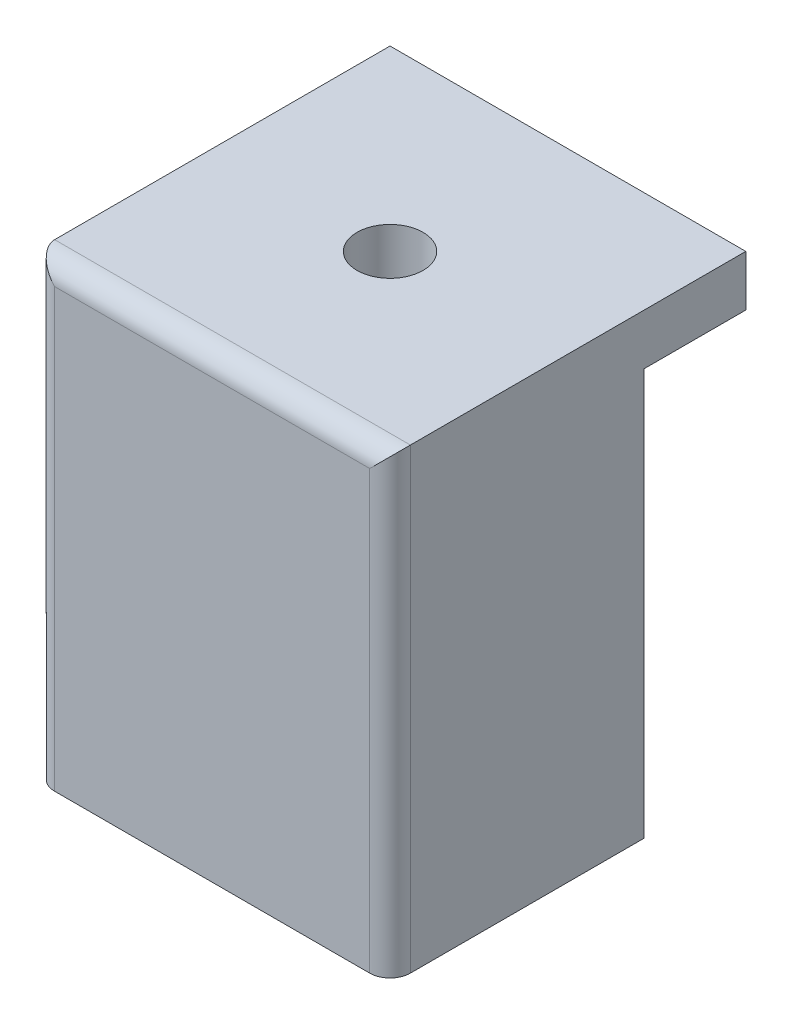
SolidWorks part; units mm, degrees
ref_plane "Front Plane" through (0, 0, 0) normal (0, 0, 1) x (1, 0, 0)
ref_plane "Top Plane" through (0, 0, 0) normal (0, 1, 0) x (1, 0, 0)
ref_plane "Right Plane" through (0, 0, 0) normal (1, 0, 0) x (0, 0, -1)
sketch "Sketch1" plane through (0, 0, 0) normal (0, 1, 0) x (1, 0, 0)
  line L0 (-17.5, 7.5) -> (-7.5, 7.5)
  line L2 (-7.5, 7.5) -> (-7.5, -7.5)
  line L3 (-7.5, -7.5) -> (7.5, -7.5)
  line L4 (7.5, 7.5) -> (7.5, -7.5)
  line L5 (-7.5, 7.5) -> (7.5, -7.5) construction
  line L6 (-7.5, -7.5) -> (7.5, 7.5) construction
  line L8 (-17.5, 7.5) -> (-17.5, -17.5)
  line L9 (-17.5, -17.5) -> (17.5, -17.5)
  line L10 (17.5, 7.5) -> (17.5, -17.5)
  line L11 (-7.5, 7.5) -> (17.5, -17.5) construction
  line L12 (-17.5, -17.5) -> (7.5, 7.5) construction
  line L13 (7.5, 7.5) -> (17.5, 7.5)
  point P0 (0, 0)
  point P6 (0, 0)
  dimension "D1" = 15
  dimension "D2" = 15
  dimension "D3" = 10
  dimension "D4" = 10
  dimension "D5" = 10
extrude "Boss-Extrude1" add sketch "Sketch1" along normal blind 45
sketch "Sketch2" plane through (0, 0, 7.5) normal (0, 0, -1) x (-1, 0, 0)
  line L0 (7.5, 45) -> (7.5, 0) construction
  line L1 (-7.5, 45) -> (7.5, 45)
  line L2 (-7.5, 45) -> (-7.5, 35)
  line L3 (-7.5, 35) -> (7.5, 35)
  line L4 (7.5, 45) -> (7.5, 35)
  line L5 (0, 20) -> (0, 0) construction
  line L6 (-7.5, 20) -> (7.5, 20) construction
  line L7 (-7.5, 45) -> (-7.5, 0) construction
  line L8 (7.5, 45) -> (7.5, 0) construction
  line L9 (0, 35) -> (0, 20) construction
  line L10 (0, 27.5) -> (7.5, 27.5) construction
  line L11 (-7.5, 20) -> (7.5, 20)
  line L12 (7.5, 10) -> (7.5, 20)
  line L13 (-7.5, 10) -> (7.5, 10)
  line L14 (-7.5, 10) -> (-7.5, 20)
  line L15 (-7.5, 0) -> (7.5, 0) construction
  dimension "D1" = 10
  dimension "D2" = 10
extrude "Boss-Extrude2" add sketch "Sketch2" along normal up to surface (15 mm away) up to face at (12.5, 22.5, -7.5)
sketch "Sketch3" plane through (0, 45, 0) normal (0, 1, 0) x (1, 0, 0)
  circle A0 centre (0, 0) radius 3.25
extrude "Cut-Extrude1" cut sketch "Sketch3" against normal up to surface (45 mm away)
sketch "Sketch4" plane through (0, 0, -7.5) normal (0, 0, -1) x (-1, 0, 0)
  line L0 (17.5, 45) -> (17.5, 0) construction
  line L1 (-17.5, 45) -> (17.5, 45)
  line L2 (-17.5, 45) -> (-17.5, 40)
  line L3 (-17.5, 40) -> (17.5, 40)
  line L4 (17.5, 45) -> (17.5, 40)
extrude "Boss-Extrude3" add sketch "Sketch4" along normal blind 10
fillet "Fillet1" radius 2 3 edges at (0, 45, 17.5) (-17.5, 22.5, 17.5) (17.5, 22.5, 17.5)
